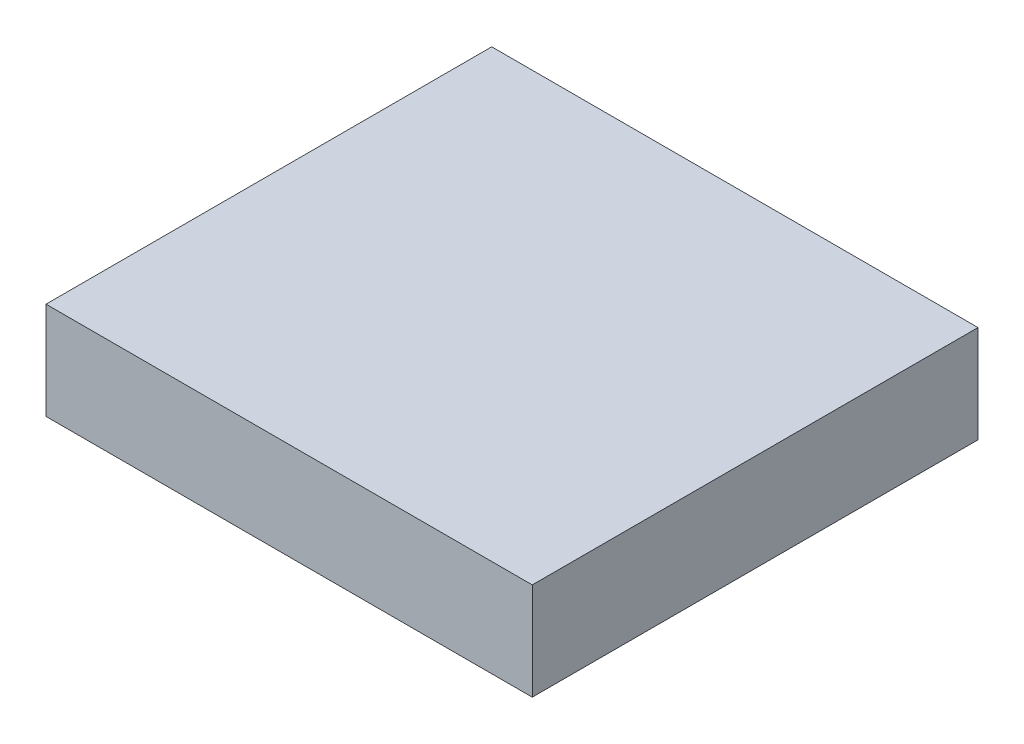
SolidWorks part; units mm, degrees
ref_plane "Front Plane" through (0, 0, 0) normal (0, 0, 1) x (1, 0, 0)
ref_plane "Top Plane" through (0, 0, 0) normal (0, 1, 0) x (1, 0, 0)
ref_plane "Right Plane" through (0, 0, 0) normal (1, 0, 0) x (0, 0, -1)
sketch "Sketch1" plane through (0, 0, 0) normal (0, 1, 0) x (1, 0, 0)
  line L1 (0, 0) -> (60, 0)
  line L2 (0, 0) -> (0, 55)
  line L3 (0, 55) -> (60, 55)
  line L4 (60, 0) -> (60, 55)
  dimension "D1" = 60
  dimension "D2" = 55
extrude "Boss-Extrude1" add sketch "Sketch1" along normal blind 12
